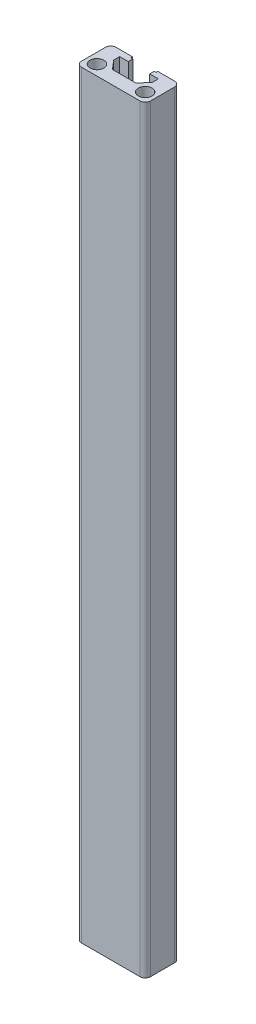
SolidWorks part; units mm, degrees
ref_plane "前视基准面" through (0, 0, 0) normal (0, 0, 1) x (1, 0, 0)
ref_plane "上视基准面" through (0, 0, 0) normal (0, 1, 0) x (1, 0, 0)
ref_plane "右视基准面" through (0, 0, 0) normal (1, 0, 0) x (0, 0, -1)
sketch "草图1" plane through (0, 0, 0) normal (0, 1, 0) x (1, 0, 0)
  line L0 (0, 0) -> (20, 0)
  line L1 (20, 0) -> (20, 10)
  line L2 (20, 10) -> (13.65, 10)
  line L3 (0, 10) -> (0, 0)
  line L4 (6.35, 10) -> (6.35, 9.5104)
  line L5 (6.35, 9.5104) -> (6.9, 9.5104)
  line L6 (6.9, 9.5104) -> (6.9, 8.2)
  line L7 (6.9, 8.2) -> (4.4, 8.2)
  line L8 (4.4, 8.2) -> (4.4, 6.4475)
  line L9 (4.4, 6.4475) -> (6.5873, 3.9)
  line L11 (15.6, 6.4475) -> (15.6, 8.2)
  line L12 (15.6, 8.2) -> (13.1, 8.2)
  line L13 (13.1, 8.2) -> (13.1, 9.5104)
  line L14 (13.1, 9.5104) -> (13.65, 9.5104)
  line L15 (13.65, 9.5104) -> (13.65, 10)
  line L16 (6.35, 10) -> (0, 10)
  line L17 (10, 0) -> (10, 13.7687) construction
  line L18 (6.5873, 3.9) -> (13.4127, 3.9)
  line L19 (13.4127, 3.9) -> (15.6, 6.4475)
  circle A0 centre (3, 3) radius 2
  circle A1 centre (17, 3) radius 2
  point P12 (10, 3.9)
  dimension "D8" = 4
  dimension "D1" = 20
  dimension "D2" = 10
  dimension "D3" = 7.3
  dimension "D4" = 6.2
  dimension "D5" = 1.8
  dimension "D6" = 4.3
  dimension "D7" = 11.2
  dimension "D9" = 3
  dimension "D10" = 14
extrude "凸台-拉伸1" add sketch "草图1" along normal blind 220
fillet "圆角1" radius 1.5 4 edges at (0, 110, -10) (0, 110, 0) (20, 110, -10) (20, 110, 0)
